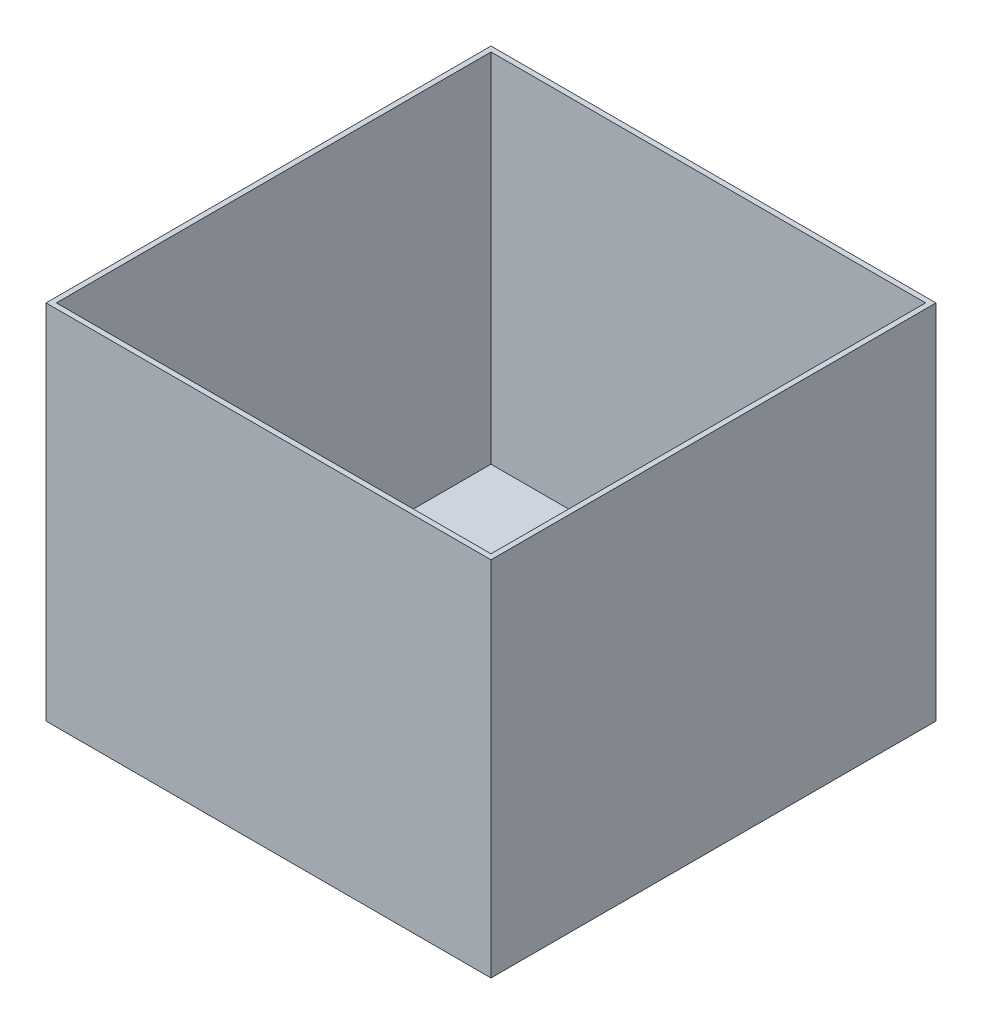
SolidWorks part; units mm, degrees
ref_plane "Спереди" through (0, 0, 0) normal (0, 0, 1) x (1, 0, 0)
ref_plane "Сверху" through (0, 0, 0) normal (0, 1, 0) x (1, 0, 0)
ref_plane "Справа" through (0, 0, 0) normal (1, 0, 0) x (0, 0, -1)
other "Configuration Table"
sketch "Эскиз1" plane through (0, -55, 0) normal (0, 1, 0) x (1, 0, 0)
  line L0 (210, 210) -> (-210, 210)
  line L1 (-210, 210) -> (-210, -210)
  line L2 (-210, -210) -> (210, -210)
  line L3 (210, -210) -> (210, 210)
  line L4 (-215, -215) -> (215, -215)
  line L5 (215, -215) -> (215, 215)
  line L6 (215, 215) -> (-215, 215)
  line L7 (-215, 215) -> (-215, -215)
  line L8 (-215, -215) -> (215, -215)
  line L9 (215, -215) -> (215, 215)
  line L10 (215, 215) -> (-215, 215)
  line L11 (-215, 215) -> (-215, -215)
  dimension "D1" = 0
  dimension "D2" = 5
extrude "Бобышка-Вытянуть1" add sketch "Эскиз1" along normal up to surface (350 mm away)
sketch "Эскиз2" plane through (0, -55, 0) normal (0, 1, 0) x (1, 0, 0)
  line L4 (-215, -215) -> (215, -215)
  line L5 (215, -215) -> (215, 215)
  line L6 (215, 215) -> (-215, 215)
  line L7 (-215, 215) -> (-215, -215)
  line L8 (-215, -215) -> (215, -215)
  line L9 (215, -215) -> (215, 215)
  line L10 (215, 215) -> (-215, 215)
  line L11 (-215, 215) -> (-215, -215)
  dimension "D1" = 0
extrude "Бобышка-Вытянуть2" add sketch "Эскиз2" along normal blind 5
